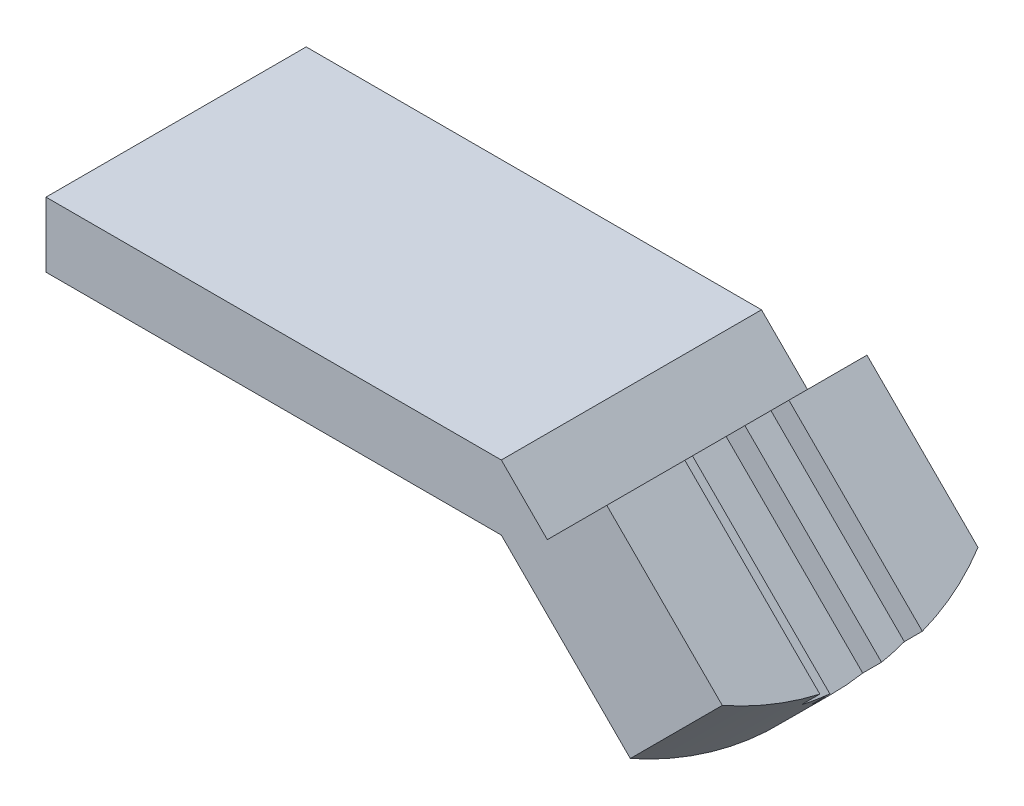
SolidWorks part; units mm, degrees
ref_plane "Front Plane" through (0, 0, 0) normal (0, 0, 1) x (1, 0, 0)
ref_plane "Top Plane" through (0, 0, 0) normal (0, 1, 0) x (1, 0, 0)
ref_plane "Right Plane" through (0, 0, 0) normal (1, 0, 0) x (0, 0, -1)
sketch "Sketch1" plane through (0, 0, 0) normal (0, 0, 1) x (1, 0, 0)
  line L0 (0, 0) -> (35, 0)
  line L1 (0, 5) -> (35, 5)
  line L3 (0, 5) -> (0, 0)
  line L4 (35, 0) -> (46.6421, -11.6421)
  line L5 (53.7132, -4.5711) -> (46.6421, -11.6421)
  line L6 (53.7132, -4.5711) -> (43.1066, 6.0355)
  line L7 (43.1066, 6.0355) -> (38.5355, 1.4645)
  line L8 (35, 5) -> (38.5355, 1.4645)
  line L9 (43.1066, 6.0355) -> (62.8289, 6.0355) construction
  dimension "D1" = 35
  dimension "D2" = 10
  dimension "5" = 5
  dimension "D3" = 15
  dimension "D4" = 20
  dimension "D5" = 45
extrude "Boss-Extrude1" add sketch "Sketch1" along normal blind 20
sketch "Sketch2" plane through (29.1421, -29.1421, 0) normal (0.7071, -0.7071, 0) x (0, 0, -1)
  line L0 (-10, 34.7487) -> (-10, 24.7487) construction
  line L1 (-20, 34.7487) -> (0, 34.7487) construction
  line L2 (-20, 24.7487) -> (0, 24.7487) construction
  line L3 (-14, 34.7487) -> (-14, 32.7487)
  line L4 (-14, 32.7487) -> (-12, 32.7487)
  line L5 (-12, 30.7487) -> (-12, 32.7487)
  line L6 (-12, 30.7487) -> (-8, 30.7487)
  line L7 (-8, 30.7487) -> (-8, 32.7926)
  line L8 (-8, 32.7926) -> (-6, 32.7926)
  line L9 (-6, 32.7926) -> (-6, 34.7487)
  dimension "D1" = 2
  dimension "D2" = 2
  dimension "D3" = 8
  dimension "D4" = 4
extrude "Cut-Extrude3" cut sketch "Sketch2" against normal through all and the other way through all contours L3 L4 L5 L6 L7 L8 L9
sketch "Sketch4" plane through (24.5711, 24.5711, 0) normal (0.7071, 0.7071, 0) x (0, 0, -1)
  line L0 (0, -41.2132) -> (0, -26.2132) construction
  line L1 (-20, -41.2132) -> (-20, -26.2132) construction
  line L2 (-12, -41.2132) -> (-8, -41.2132) construction
  arc A0 (0, -38.2839) -> (-20, -38.7699) centre (-10.4207, -21.2132) cw
  dimension "D1" = 20
extrude "Cut-Extrude4" cut sketch "Sketch4" against normal through all and the other way through all
